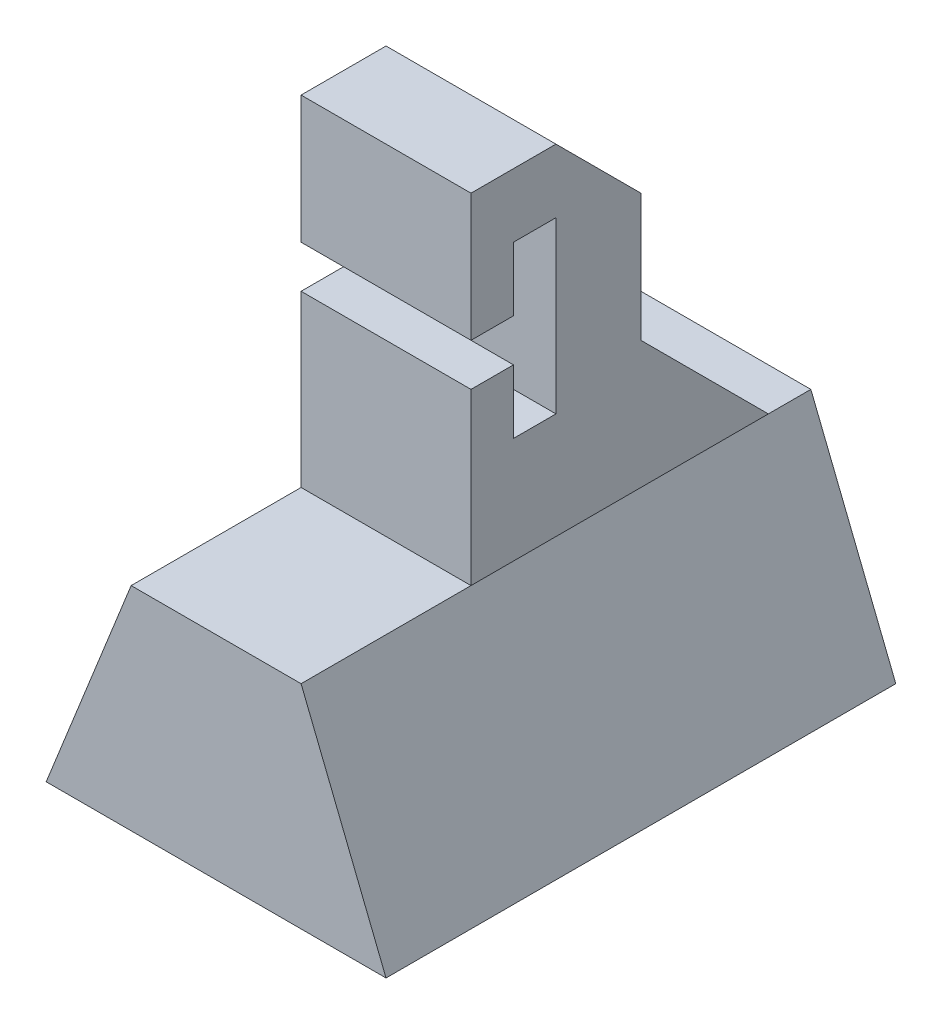
SolidWorks part; units mm, degrees
ref_plane "Front Plane" through (0, 0, 0) normal (0, 0, 1) x (1, 0, 0)
ref_plane "Top Plane" through (0, 0, 0) normal (0, 1, 0) x (1, 0, 0)
ref_plane "Right Plane" through (0, 0, 0) normal (1, 0, 0) x (0, 0, -1)
sketch "Sketch1" plane through (0, 0, 0) normal (0, 0, 1) x (1, 0, 0)
  line L0 (-3.1304, -2.6087) -> (4.8696, -2.6087)
  line L1 (4.8696, -2.6087) -> (2.8696, 2.3913)
  line L2 (2.8696, 2.3913) -> (-1.1304, 2.3913)
  line L3 (-1.1304, 2.3913) -> (-3.1304, -2.6087)
  dimension "D1" = 8
  dimension "D2" = 4
  dimension "D3" = 2
  dimension "D4" = 5
extrude "Boss-Extrude1" add sketch "Sketch1" along normal blind 12
sketch "Sketch2" plane through (0, 2.3913, 0) normal (0, 1, 0) x (1, 0, 0)
  line L0 (-1.1304, -12) -> (-1.1304, 0) construction
  line L1 (-1.1304, -4) -> (2.8696, -4)
  line L2 (-1.1304, -4) -> (-1.1304, -8)
  line L3 (-1.1304, -8) -> (2.8696, -8)
  line L4 (2.8696, -4) -> (2.8696, -8)
  line L5 (2.8696, -12) -> (2.8696, 0) construction
  line L6 (2.8696, 0) -> (-1.1304, 0) construction
  line L7 (2.8696, -12) -> (-1.1304, -12) construction
  dimension "D1" = 4
  dimension "D2" = 4
extrude "Boss-Extrude2" add sketch "Sketch2" along normal blind 8
chamfer "Chamfer1" distance 3 angle 45 1 edges at (0.8696, 2.3913, 4)
sketch "Sketch3" plane through (2.8696, 0, 0) normal (1, 0, 0) x (0, 0, -1)
  line L0 (-8, 10.3913) -> (-4, 10.3913) construction
  line L1 (-7, 8.8913) -> (-6, 8.8913)
  line L2 (-7, 8.8913) -> (-7, 7.3913)
  line L3 (-7, 4.8913) -> (-6, 4.8913)
  line L4 (-6, 8.8913) -> (-6, 4.8913)
  line L5 (-8, 10.3913) -> (-8, 2.3913) construction
  line L6 (-7, 6.3913) -> (-7, 4.8913)
  line L7 (-7, 7.3913) -> (-8, 7.3913)
  line L9 (-7, 6.3913) -> (-8, 6.3913)
  line L10 (-8, 7.3913) -> (-8, 6.3913)
  dimension "D1" = 4
  dimension "D2" = 1.5
  dimension "D3" = 1
  dimension "D4" = 1
  dimension "D5" = 1.5
  dimension "D6" = 1.5
extrude "Cut-Extrude1" cut sketch "Sketch3" against normal blind 18
chamfer "Chamfer2" distance 2 angle 45 1 edges at (0.8696, 10.3913, 4)
